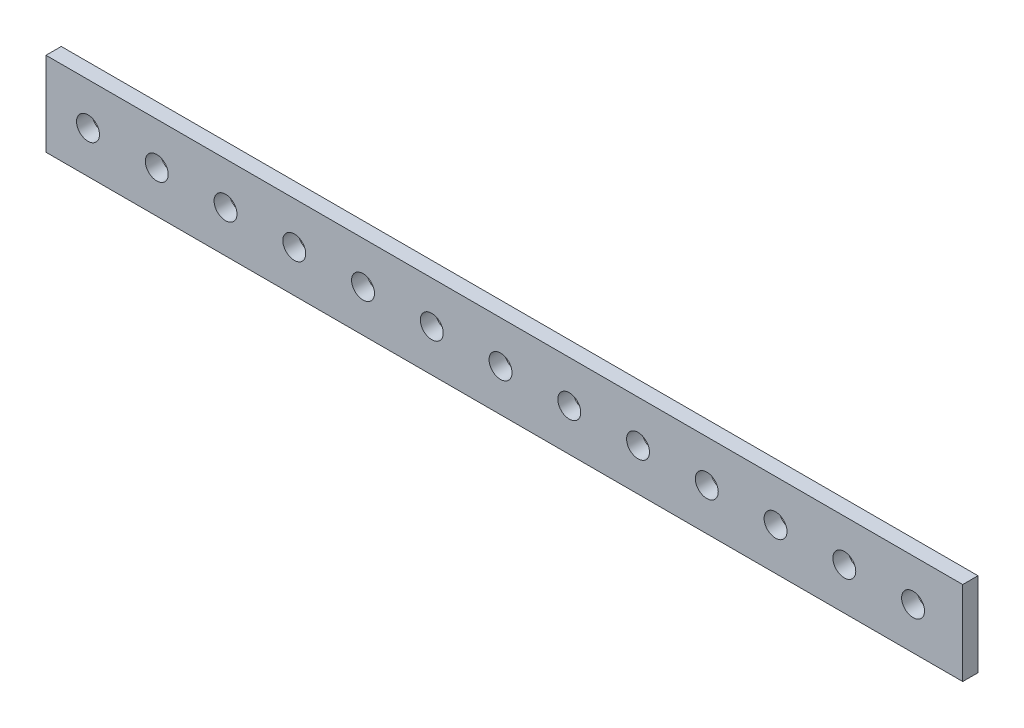
SolidWorks part; units mm, degrees
ref_plane "Front Plane" through (0, 0, 0) normal (0, 0, 1) x (1, 0, 0)
ref_plane "Top Plane" through (0, 0, 0) normal (0, 1, 0) x (1, 0, 0)
ref_plane "Right Plane" through (0, 0, 0) normal (1, 0, 0) x (0, 0, -1)
sketch "Sketch1" plane through (0, 0, 0) normal (0, 0, 1) x (1, 0, 0)
  line L1 (0, 0) -> (1200, 0)
  line L2 (0, 0) -> (0, 110)
  line L3 (0, 110) -> (1200, 110)
  line L4 (1200, 0) -> (1200, 110)
  dimension "D1" = 1200
  dimension "D2" = 110
extrude "Boss-Extrude1" add sketch "Sketch1" along normal blind 20
sketch "Sketch3" plane through (0, 0, 20) normal (0, 0, 1) x (1, 0, 0)
  line L0 (1200, 110) -> (0, 110) construction
  line L1 (0, 110) -> (0, 0) construction
  circle A0 centre (55, 55) radius 15
  point P6 (0, 0)
  point P7 (55, 55)
  point P8 (55, 55)
  dimension "D3" = 30
  dimension "D1" = 55
  dimension "D2" = 55
extrude "Cut-Extrude1" cut sketch "Sketch3" against normal through all
pattern_linear "LPattern1" count 13 spacing 90 along (1, 0, 0) of "Cut-Extrude1"
